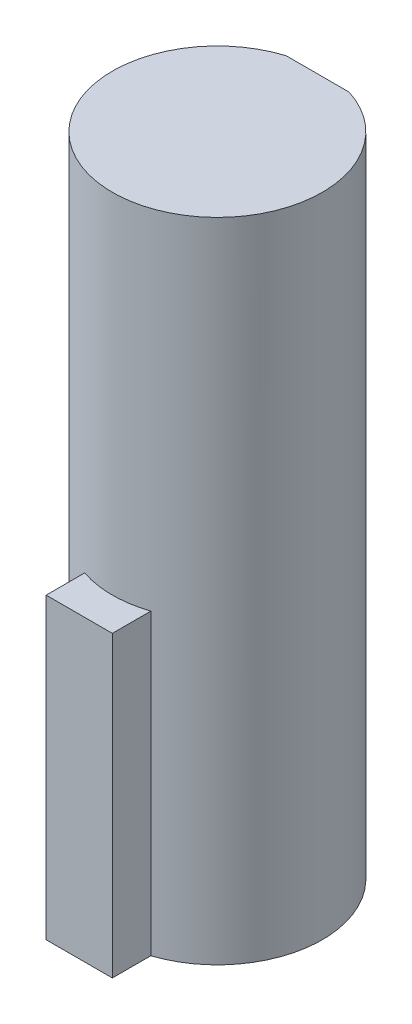
SolidWorks part; units mm, degrees
ref_plane "Front Plane" through (0, 0, 0) normal (0, 0, 1) x (1, 0, 0)
ref_plane "Top Plane" through (0, 0, 0) normal (0, 1, 0) x (1, 0, 0)
ref_plane "Right Plane" through (0, 0, 0) normal (1, 0, 0) x (0, 0, -1)
sketch "Sketch1" plane through (0, 0, 0) normal (0, 1, 0) x (1, 0, 0)
  line L0 (-2.5, 0) -> (2.5, 0)
  line L2 (2.5, 9.8011) -> (2.5, -9.8011) construction
  line L3 (2.5, -9.8011) -> (-2.5, -9.8011)
  line L4 (-2.5, 9.8011) -> (-2.5, -9.8011) construction
  line L5 (2.5, 9.8011) -> (-2.5, -9.8011) construction
  line L6 (2.5, -9.8011) -> (-2.5, 9.8011) construction
  line L7 (-2.5, 0) -> (-2.5, -9.8011) construction
  line L8 (2.5, 0) -> (2.5, -9.8011) construction
  line L9 (-2.5, -7.0711) -> (-2.5, -9.8011)
  line L10 (2.5, -7.0711) -> (2.5, -9.8011)
  line L11 (-2.3, -6.9282) -> (-2.3, -9.6011)
  line L12 (2.3, -9.6011) -> (-2.3, -9.6011)
  line L13 (2.3, -6.9282) -> (2.3, -9.6011)
  arc A0 (2.5, -7.0711) -> (-2.5, -7.0711) centre (0, 0) ccw
  arc A1 (2.3, -6.9282) -> (-2.3, -6.9282) centre (0, 0) ccw
  dimension "D1" = 15
  dimension "D2" = 5
  dimension "D3" = 2.73
  dimension "D4" = 0.2
extrude "Boss-Extrude1" add sketch "Sketch1" along normal blind 20.75
sketch "Sketch2" plane through (0, 20.75, 0) normal (0, 1, 0) x (1, 0, 0)
  circle A0 centre (0, 0) radius 7.3
  dimension "D1" = 14.6
extrude "Boss-Extrude2" add sketch "Sketch2" along normal blind 24.25
sketch "Sketch3" plane through (0, 45, 0) normal (0, 1, 0) x (1, 0, 0)
  line L0 (-2.5, 6.9649) -> (2.5, 6.9649)
  arc A0 (2.5, 6.9649) -> (-2.5, 6.9649) centre (0, 0) ccw
  dimension "D1" = 14.8
  dimension "D2" = 5
extrude "Cut-Extrude1" cut sketch "Sketch3" against normal blind 50
